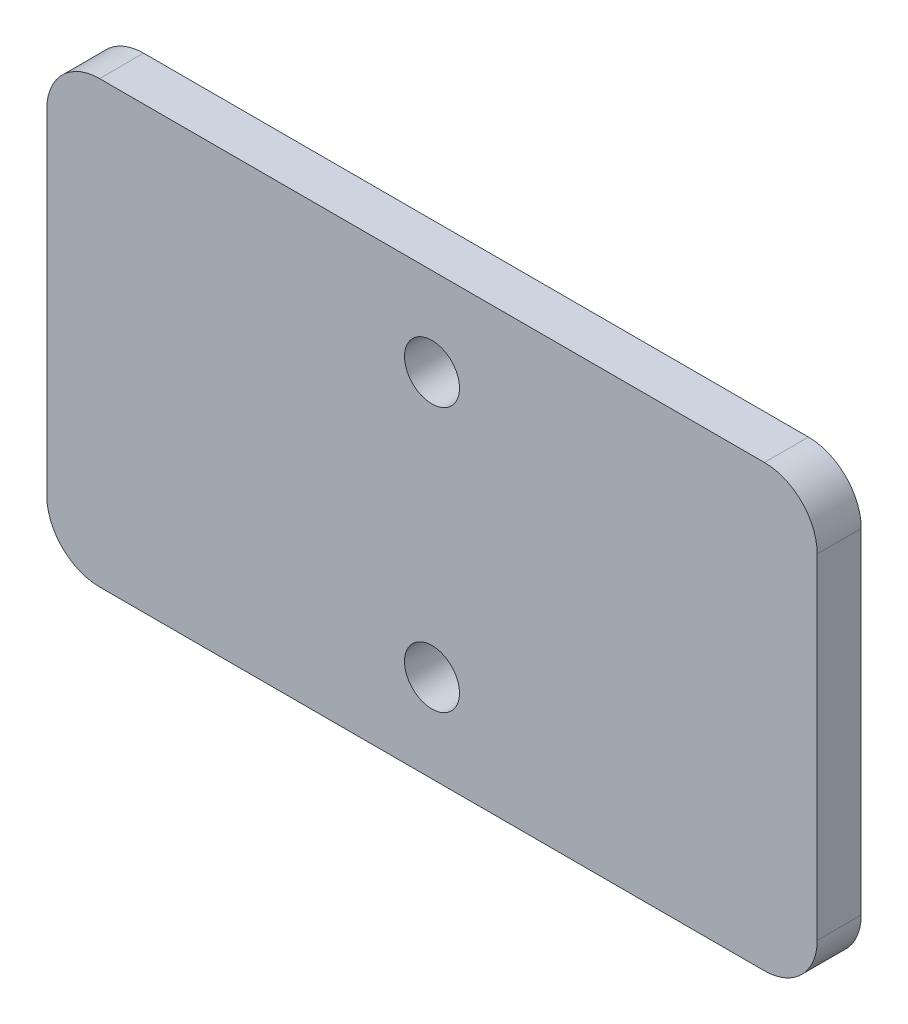
SolidWorks part; units mm, degrees
ref_plane "Plan de face" through (0, 0, 0) normal (0, 0, 1) x (1, 0, 0)
ref_plane "Plan de dessus" through (0, 0, 0) normal (0, 1, 0) x (1, 0, 0)
ref_plane "Plan de droite" through (0, 0, 0) normal (1, 0, 0) x (0, 0, -1)
sketch "Esquisse1" plane through (0, 0, 0) normal (0, 0, 1) x (1, 0, 0)
  line L1 (-87.5, 50) -> (87.5, 50)
  line L2 (-87.5, 50) -> (-87.5, -50)
  line L3 (-87.5, -50) -> (87.5, -50)
  line L4 (87.5, 50) -> (87.5, -50)
  line L5 (-87.5, 50) -> (87.5, -50) construction
  line L6 (-87.5, -50) -> (87.5, 50) construction
  circle A0 centre (0, 30) radius 6.25
  circle A1 centre (0, -30) radius 6.25
  point P0 (0, 0)
  point P10 (0, -30)
  dimension "D3" = 12.5
  dimension "D4" = 12.5
  dimension "D1" = 175
  dimension "D2" = 100
  dimension "D5" = 60
  dimension "D6" = 20
  dimension "D7" = 87.5
extrude "Boss.-Extru.1" add sketch "Esquisse1" along normal blind 10
fillet "Congé1" radius 12 4 edges at (-87.5, 50, 5) (87.5, 50, 5) (87.5, -50, 5) (-87.5, -50, 5)
